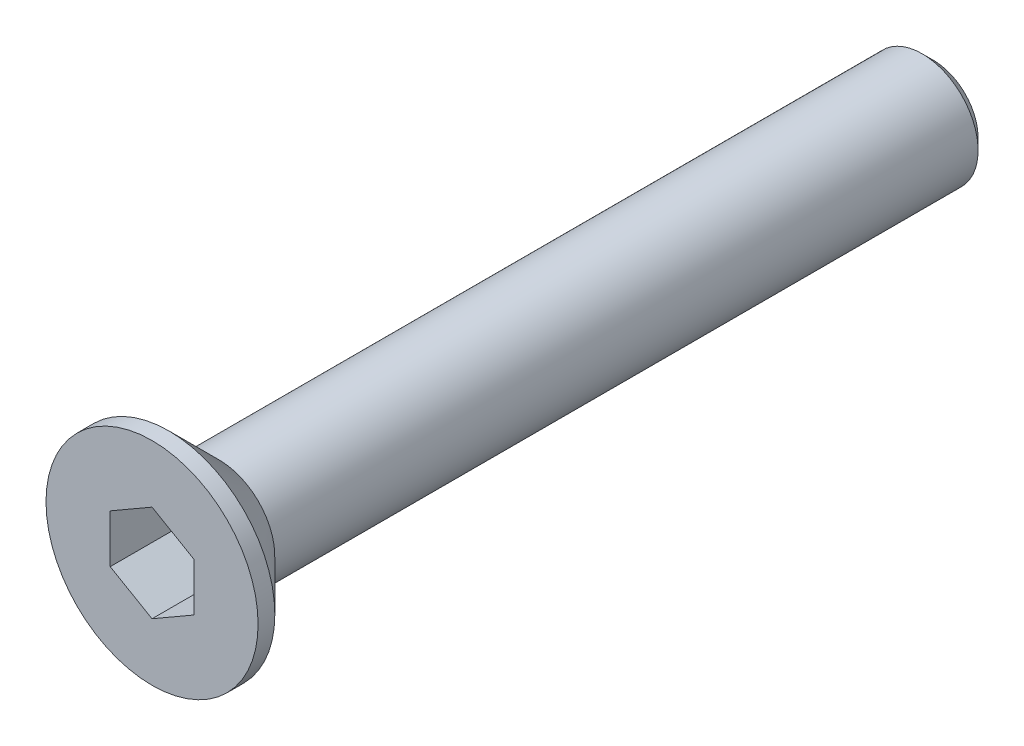
SolidWorks part; units mm, degrees
ref_plane "前视基准面" through (0, 0, 0) normal (0, 0, 1) x (1, 0, 0)
ref_plane "上视基准面" through (0, 0, 0) normal (0, 1, 0) x (1, 0, 0)
ref_plane "右视基准面" through (0, 0, 0) normal (1, 0, 0) x (0, 0, -1)
sketch "草图1" plane through (0, 0, 0) normal (1, 0, 0) x (0, 0, -1)
  line L0 (7, 0) -> (-7, 0)
  line L1 (-7, 0) -> (-7, 1.9)
  line L2 (-7, 1.9) -> (-6.7, 1.9)
  line L3 (-6.7, 1.9) -> (-5.8, 1)
  line L4 (-5.8, 1) -> (7, 1)
  line L5 (7, 1) -> (7, 0)
  point P4 (0, 0)
  dimension "D1" = 14
  dimension "D2" = 1.2
  dimension "D3" = 45
  dimension "D4" = 1
  dimension "D5" = 1.9
revolve "旋转1" add sketch "草图1" angle 360 about L0
sketch "草图2" plane through (0, 0, 7) normal (0, 0, 1) x (1, 0, 0)
  line L1 (0, 0.866) -> (-0.75, 0.433)
  line L2 (-0.75, 0.433) -> (-0.75, -0.433)
  line L3 (-0.75, -0.433) -> (0, -0.866)
  line L4 (0, -0.866) -> (0.75, -0.433)
  line L5 (0.75, -0.433) -> (0.75, 0.433)
  line L6 (0.75, 0.433) -> (0, 0.866)
  circle A0 centre (0, 0) radius 0.75 construction
  dimension "D1" = 1.5
extrude "切除-拉伸1" cut sketch "草图2" against normal blind 1.5
chamfer "倒角1" distance 0.2 angle 45 1 edges at (-1, 0, -7)
